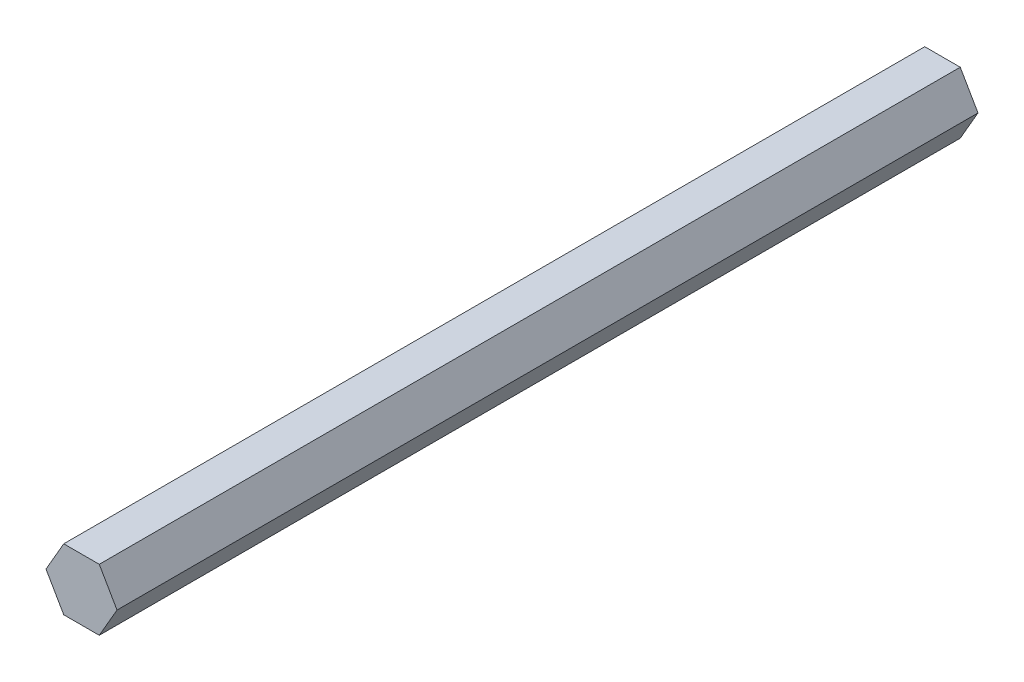
SolidWorks part; units mm, degrees
ref_plane "Front Plane" through (0, 0, 0) normal (0, 0, 1) x (1, 0, 0)
ref_plane "Top Plane" through (0, 0, 0) normal (0, 1, 0) x (1, 0, 0)
ref_plane "Right Plane" through (0, 0, 0) normal (1, 0, 0) x (0, 0, -1)
sketch "Sketch1" plane through (0, 0, 0) normal (0, 0, 1) x (1, 0, 0)
  line L0 (0, 12.7) -> (7.3323, 12.7)
  line L1 (7.3323, 12.7) -> (10.9985, 6.35)
  line L2 (10.9985, 6.35) -> (7.3323, 0)
  line L3 (7.3323, 0) -> (0, 0)
  line L4 (0, 0) -> (-3.6662, 6.35)
  line L5 (-3.6662, 6.35) -> (0, 12.7)
  point P2 (0, 0)
  point P7 (-3.9241, -5.0316)
  point P8 (0, 0)
  point P10 (0, 0)
  point P11 (-2.7792, 12.7)
  point P12 (4.9115, 0)
  point P13 (4.7359, 0)
  point P14 (-3.8772, 6.4464)
  dimension "D1" = 12.7
  dimension "D2" = 12.7
  dimension "D3" = 12.7
  dimension "D4" = 6.35
extrude "Boss-Extrude1" add sketch "Sketch1" along normal blind 177.8
